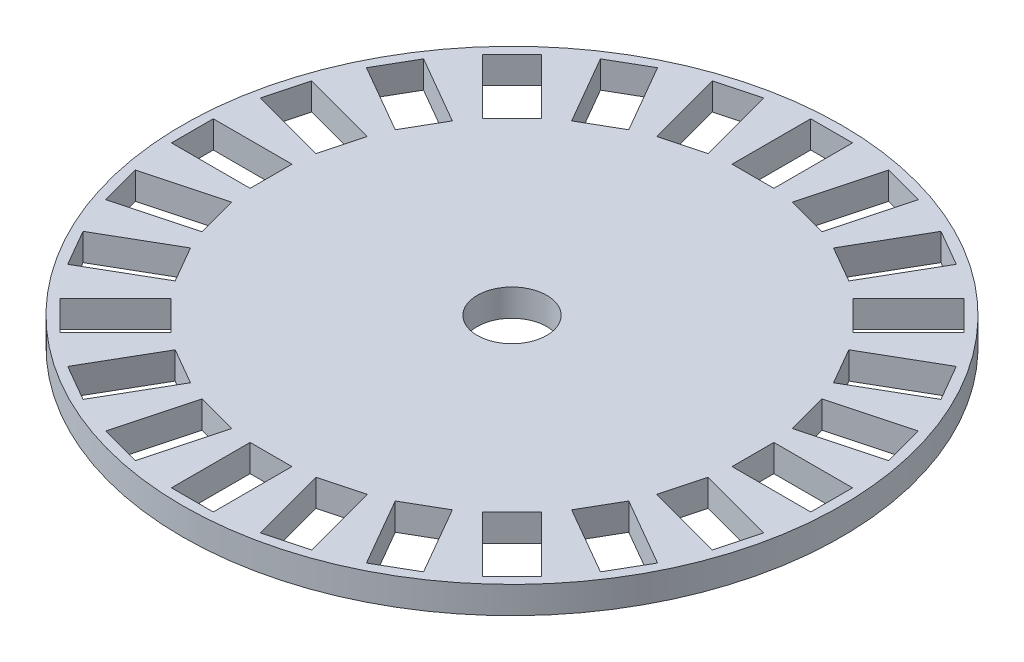
SolidWorks part; units mm, degrees
ref_plane "Front Plane" through (0, 0, 0) normal (0, 0, 1) x (1, 0, 0)
ref_plane "Top Plane" through (0, 0, 0) normal (0, 1, 0) x (1, 0, 0)
ref_plane "Right Plane" through (0, 0, 0) normal (1, 0, 0) x (0, 0, -1)
sketch "Sketch1" plane through (0, 0, 0) normal (0, 1, 0) x (1, 0, 0)
  circle A0 centre (0, 0) radius 36.5
  dimension "D1" = 73
extrude "Boss-Extrude1" add sketch "Sketch1" along normal blind 3
sketch "Sketch2" plane through (0, 3, 0) normal (0, 1, 0) x (1, 0, 0)
  circle A0 centre (0, 0) radius 3.85
  dimension "D1" = 7.7
extrude "Cut-Extrude1" cut sketch "Sketch2" against normal through all
sketch "Sketch3" plane through (0, 3, 0) normal (0, 1, 0) x (1, 0, 0)
  line L0 (0, -1.65) -> (0, 1.65) construction
  line L1 (-2.3159, 26.6879) -> (2.3159, 26.6879)
  line L2 (-2.3159, 26.6879) -> (-2.3159, 35.4003)
  line L3 (-2.3159, 35.4003) -> (2.3159, 35.4003)
  line L4 (2.3159, 26.6879) -> (2.3159, 35.4003)
  line L5 (-2.3159, 26.6879) -> (2.3159, 35.4003) construction
  line L6 (-2.3159, 35.4003) -> (2.3159, 26.6879) construction
  circle A0 centre (0, 0) radius 34.5 construction
  circle A1 centre (0, 0) radius 36.5 construction
  point P5 (0, 31.0441)
  dimension "D1" = 2
extrude "Cut-Extrude2" cut sketch "Sketch3" against normal through all
pattern_circular "CirPattern1" count 24 every 15 about axis through (0, 0, 0) along (0, 1, 0) of "Cut-Extrude2"
